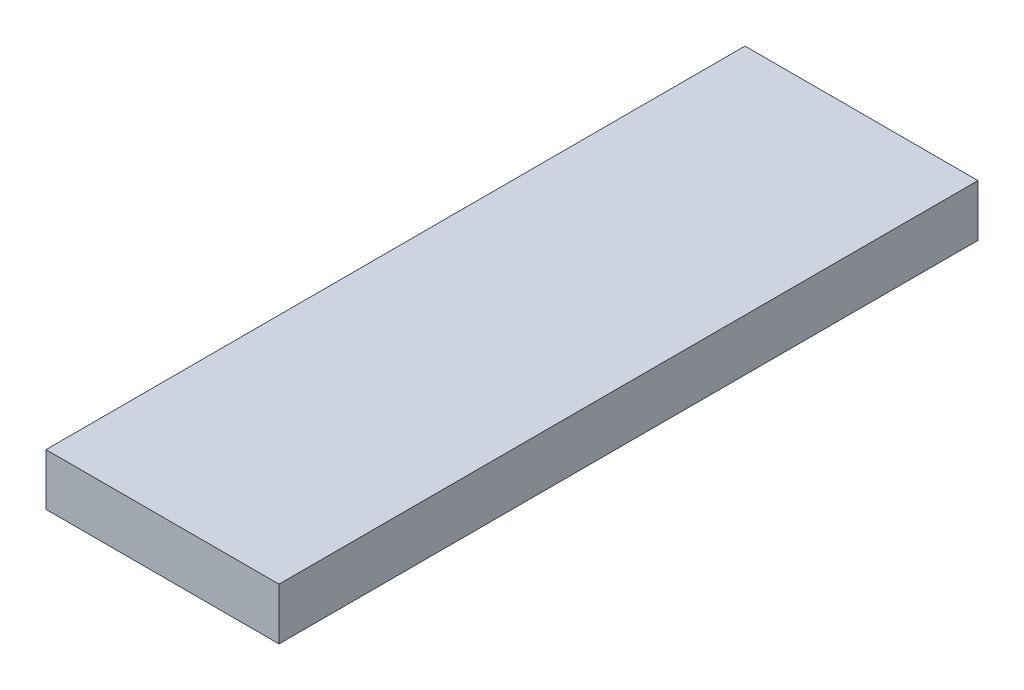
SolidWorks part; units mm, degrees
ref_plane "Front Plane" through (0, 0, 0) normal (0, 0, 1) x (1, 0, 0)
ref_plane "Top Plane" through (0, 0, 0) normal (0, 1, 0) x (1, 0, 0)
ref_plane "Right Plane" through (0, 0, 0) normal (1, 0, 0) x (0, 0, -1)
sketch "Sketch1" plane through (0, 0, 0) normal (0, 1, 0) x (1, 0, 0)
  line L1 (4.5, -13.5) -> (-4.5, -13.5)
  line L2 (4.5, -13.5) -> (4.5, 13.5)
  line L3 (4.5, 13.5) -> (-4.5, 13.5)
  line L4 (-4.5, -13.5) -> (-4.5, 13.5)
  line L5 (4.5, -13.5) -> (-4.5, 13.5) construction
  line L6 (4.5, 13.5) -> (-4.5, -13.5) construction
  point P0 (0, 0)
  dimension "D1" = 9
  dimension "D2" = 27
extrude "Boss-Extrude1" add sketch "Sketch1" along normal blind 2
